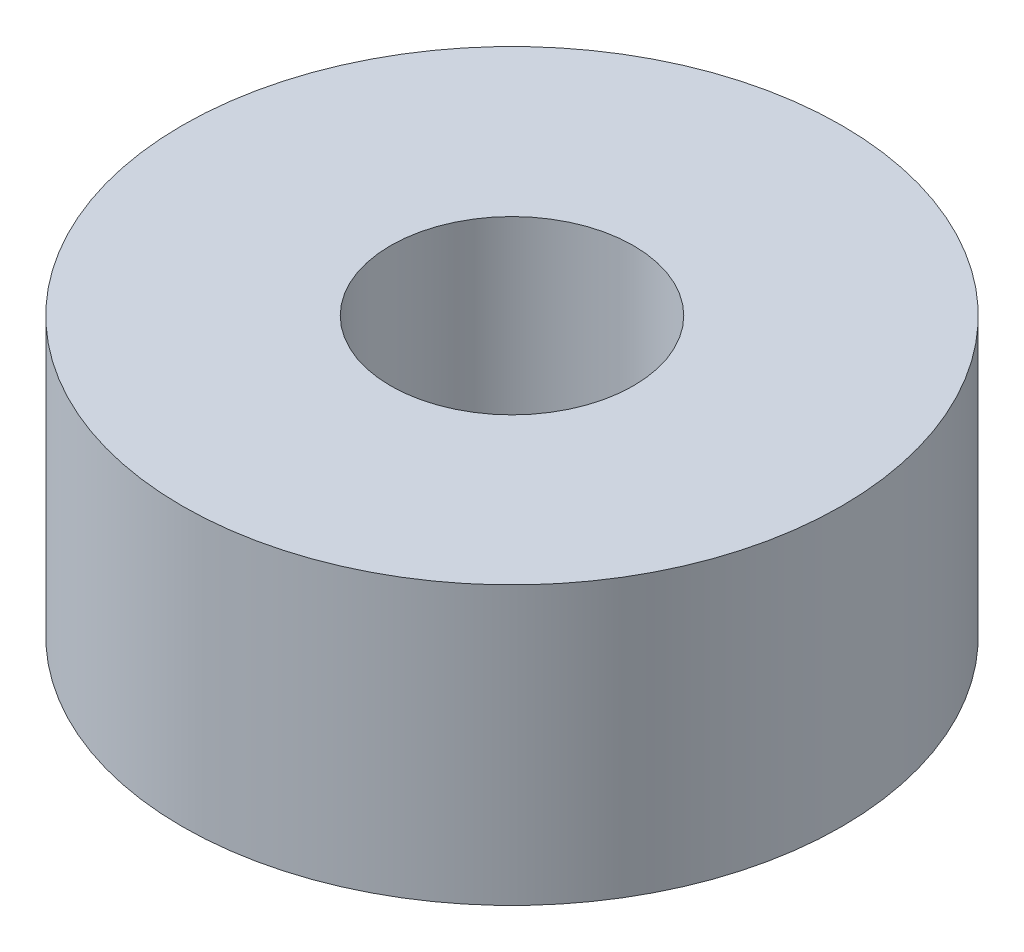
SolidWorks part; units mm, degrees
ref_plane "Front Plane" through (0, 0, 0) normal (0, 0, 1) x (1, 0, 0)
ref_plane "Top Plane" through (0, 0, 0) normal (0, 1, 0) x (1, 0, 0)
ref_plane "Right Plane" through (0, 0, 0) normal (1, 0, 0) x (0, 0, -1)
sketch "Sketch1" plane through (0, 0, 0) normal (0, 1, 0) x (1, 0, 0)
  circle A0 centre (0, 0) radius 4.75
  dimension "D1" = 9.5
extrude "Boss-Extrude1" add sketch "Sketch1" along normal blind 4
sketch "Sketch2" plane through (0, 4, 0) normal (0, 1, 0) x (1, 0, 0)
  circle A0 centre (0, 0) radius 1.75
  dimension "D1" = 3.5
extrude "Cut-Extrude1" cut sketch "Sketch2" against normal through all
sketch "Sketch3" plane through (0, 0, 0) normal (0, -1, 0) x (1, 0, 0)
  line L1 (-5, -5) -> (25, -5)
  line L2 (-5, -5) -> (-5, 25)
  line L3 (-5, 25) -> (25, 25)
  line L4 (25, -5) -> (25, 25)
  dimension "D1" = 30
  dimension "D2" = 30
  dimension "D3" = 5
  dimension "D4" = 5
extrude "Boss-Extrude2" [suppressed] add sketch "Sketch3" along normal blind 4
pattern_linear "LPattern1" [suppressed] count 2 spacing 12 count 2 spacing 12
sketch "Sketch4" [suppressed] plane through (0, -4, 0) normal (0, -1, 0) x (1, 0, 0)
  line L4 (-5, 25) -> (-5, -5)
  line L5 (-5, -5) -> (25, -5)
  line L6 (25, -5) -> (25, 25)
  line L7 (25, 25) -> (-5, 25)
  line L8 (-5, 25) -> (-5, -5)
  line L9 (-5, -5) -> (25, -5)
  line L10 (25, -5) -> (25, 25)
  line L11 (25, 25) -> (-5, 25)
  dimension "D1" = 0
extrude "Cut-Extrude2" [suppressed] cut sketch "Sketch4" against normal blind 4
